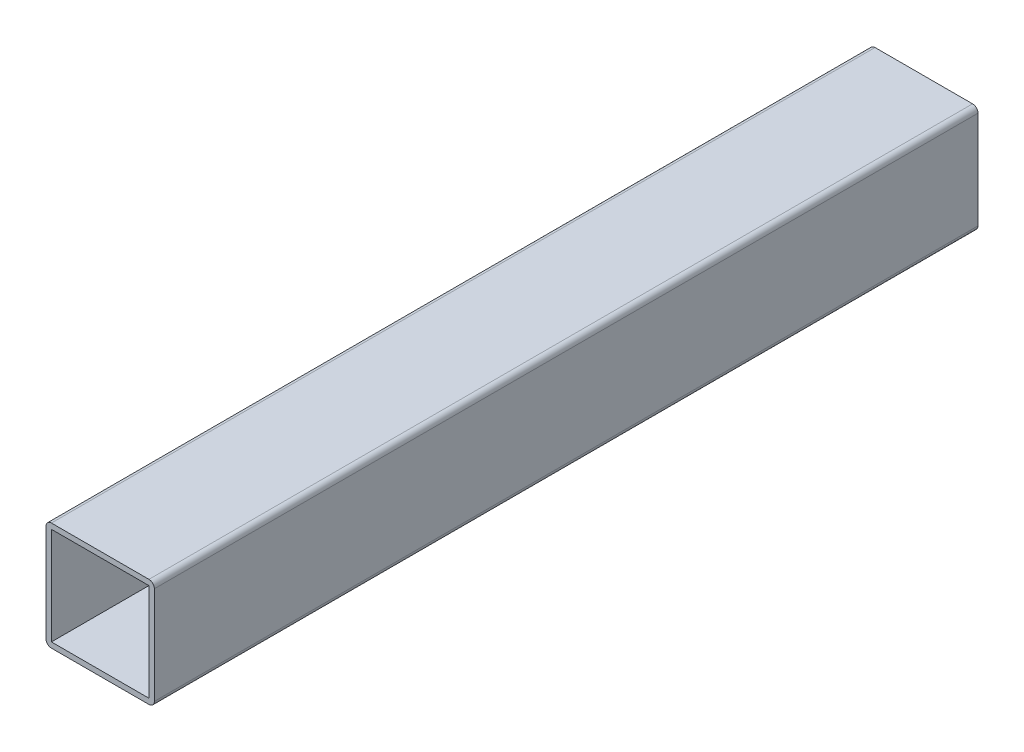
SolidWorks part; units mm, degrees
ref_plane "Front Plane" through (0, 0, 0) normal (0, 0, 1) x (1, 0, 0)
ref_plane "Top Plane" through (0, 0, 0) normal (0, 1, 0) x (1, 0, 0)
ref_plane "Right Plane" through (0, 0, 0) normal (1, 0, 0) x (0, 0, -1)
sketch "Sketch1" plane through (0, 0, 0) normal (0, 0, 1) x (1, 0, 0)
  line L0 (-45, 45) -> (45, 45)
  line L1 (-45, -50) -> (45, -50)
  line L2 (-50, -45) -> (-50, 45)
  line L3 (-45, 50) -> (45, 50)
  line L4 (50, -45) -> (50, 45)
  line L5 (-50, -50) -> (50, 50) construction
  line L6 (-50, 50) -> (50, -50) construction
  line L7 (45, -45) -> (45, 45)
  line L8 (-45, -45) -> (45, -45)
  line L9 (-45, -45) -> (-45, 45)
  arc A0 (-45, 50) -> (-50, 45) centre (-45, 45) ccw
  arc A1 (-50, -45) -> (-45, -50) centre (-45, -45) ccw
  arc A2 (45, -50) -> (50, -45) centre (45, -45) ccw
  arc A3 (50, 45) -> (45, 50) centre (45, 45) ccw
  arc A4 (45, 45) -> (45, 45) centre (45, 45) ccw
  arc A5 (45, -45) -> (45, -45) centre (45, -45) ccw
  arc A6 (-45, -45) -> (-45, -45) centre (-45, -45) ccw
  arc A7 (-45, 45) -> (-45, 45) centre (-45, 45) ccw
  point P0 (0, 0)
  dimension "D2" = 5
  dimension "D1" = 100
  dimension "D3" = 5
extrude "Boss-Extrude1" add sketch "Sketch1" along normal blind 760
